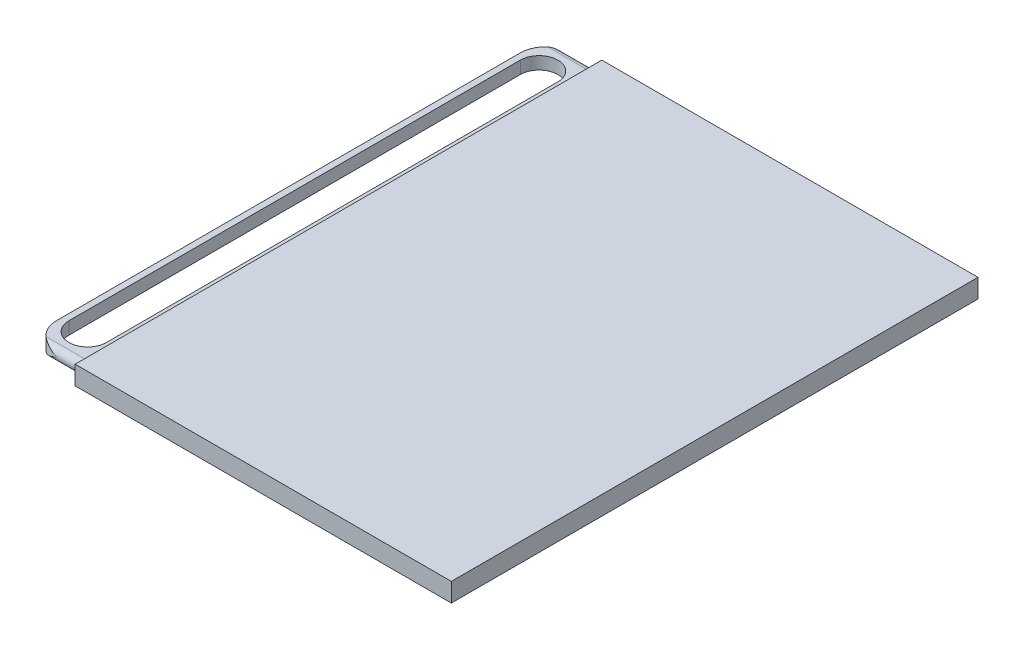
SolidWorks part; units mm, degrees
ref_plane "Front Plane" through (0, 0, 0) normal (0, 0, 1) x (1, 0, 0)
ref_plane "Top Plane" through (0, 0, 0) normal (0, 1, 0) x (1, 0, 0)
ref_plane "Right Plane" through (0, 0, 0) normal (1, 0, 0) x (0, 0, -1)
sketch "Sketch1" plane through (0, 0, 0) normal (0, 1, 0) x (1, 0, 0)
  line L0 (0, 0) -> (-150, 0)
  line L1 (0, 0) -> (0, -210)
  line L2 (0, -210) -> (-150, -210)
  line L3 (-150, 0) -> (-150, -55)
  line L4 (-150, -155) -> (-150, -210)
  line L8 (-150, -55) -> (-150, -155)
  dimension "D1" = 150
  dimension "D2" = 210
  dimension "D3" = 55
  dimension "D6" = 55
extrude "Boss-Extrude1" add sketch "Sketch1" along normal blind 7.5
sketch "Sketch2" plane through (-150, 0, 0) normal (-1, 0, 0) x (0, 0, 1)
  line L0 (0, 7.5) -> (210, 7.5) construction
  line L1 (210, 7.5) -> (210, 0) construction
  line L2 (0, 7.5) -> (0, 0) construction
  line L3 (5, 6.25) -> (205, 6.25)
  line L4 (5, 1.25) -> (205, 1.25)
  circle A0 centre (5, 3.75) radius 2.5
  circle A1 centre (205, 3.75) radius 2.5
  point P12 (0, 0)
  point P13 (0, 0)
  point P14 (0, 0)
  point P15 (0, 0)
  point P18 (128.8947, 1.25)
  point P19 (130.8503, 6.25)
  point P20 (162.9332, 1.25)
  point P21 (158.6564, 6.25)
  point P22 (205, 1.25)
  point P23 (206.3045, 6.25)
  point P24 (205, 6.25)
  dimension "D1" = 5
  dimension "D2" = 5
  dimension "D3" = 5
  dimension "D4" = 5
  dimension "D5" = 3.75
extrude "Boss-Extrude2" add sketch "Sketch2" along normal blind 20 contours A1 L3 A0 L4 | A1 | A0
sketch "Sketch3" plane through (0, 6.25, 0) normal (0, 1, 0) x (1, 0, 0)
  line L0 (-170, -205) -> (-150, -205) construction
  line L1 (-170, -5) -> (-150, -5) construction
  line L2 (-167.5, -15) -> (-167.5, -195)
  line L3 (-152.5, -15) -> (-152.5, -195)
  line L4 (-150, -207.5) -> (-160, -207.5)
  line L5 (-170, -197.5) -> (-170, -12.5)
  line L6 (-160, -2.5) -> (-150, -2.5)
  line L7 (-150, -2.5) -> (-150, -207.5)
  line L8 (-160, -207.5) -> (-170, -207.5)
  line L9 (-170, -207.5) -> (-170, -197.5)
  line L10 (-170, -12.5) -> (-170, -2.5)
  line L11 (-170, -2.5) -> (-160, -2.5)
  circle A0 centre (-160, -15) radius 7.5
  circle A1 centre (-160, -195) radius 7.5
  arc A2 (-170, -197.5) -> (-160, -207.5) centre (-160, -197.5) ccw
  arc A3 (-160, -2.5) -> (-170, -12.5) centre (-160, -12.5) ccw
  point P8 (-160, -5)
  point P23 (-170, -207.5)
  point P26 (-170, -2.5)
  dimension "D3" = 15
  dimension "D4" = 15
  dimension "D5" = 10
  dimension "D1" = 10
  dimension "D2" = 10
extrude "Cut-Extrude1" cut sketch "Sketch3" against normal through all contours A1 L3 A0 L2 | A0 | A1
sketch "Sketch4" plane through (0, 6.25, 0) normal (0, 1, 0) x (1, 0, 0)
  line L0 (-150, -2.5) -> (-160, -2.5)
  line L1 (-170, -12.5) -> (-170, -197.5)
  line L2 (-160, -207.5) -> (-150, -207.5)
  line L3 (-150, -207.5) -> (-150, -2.5)
  line L4 (-160, -207.5) -> (-170, -207.5)
  line L5 (-170, -207.5) -> (-170, -197.5)
  line L6 (-170, -12.5) -> (-170, -2.5)
  line L7 (-170, -2.5) -> (-160, -2.5)
  arc A0 (-160, -207.5) -> (-170, -197.5) centre (-160, -197.5) cw
  arc A1 (-170, -12.5) -> (-160, -2.5) centre (-160, -12.5) cw
  point P10 (-170, -207.5)
  point P13 (-170, -2.5)
  line M12 (-150, -5) -> (-170, -5)
  line M13 (-170, -5) -> (-170, -205)
  line M14 (-170, -205) -> (-150, -205)
  dimension "D1" = 10
extrude "Cut-Extrude2" cut sketch "Sketch4" against normal blind 20 contours A1 L7 L6 M12 | A1 M13 M12 | L4 A0 L5 M14 | A0 M14 M13
